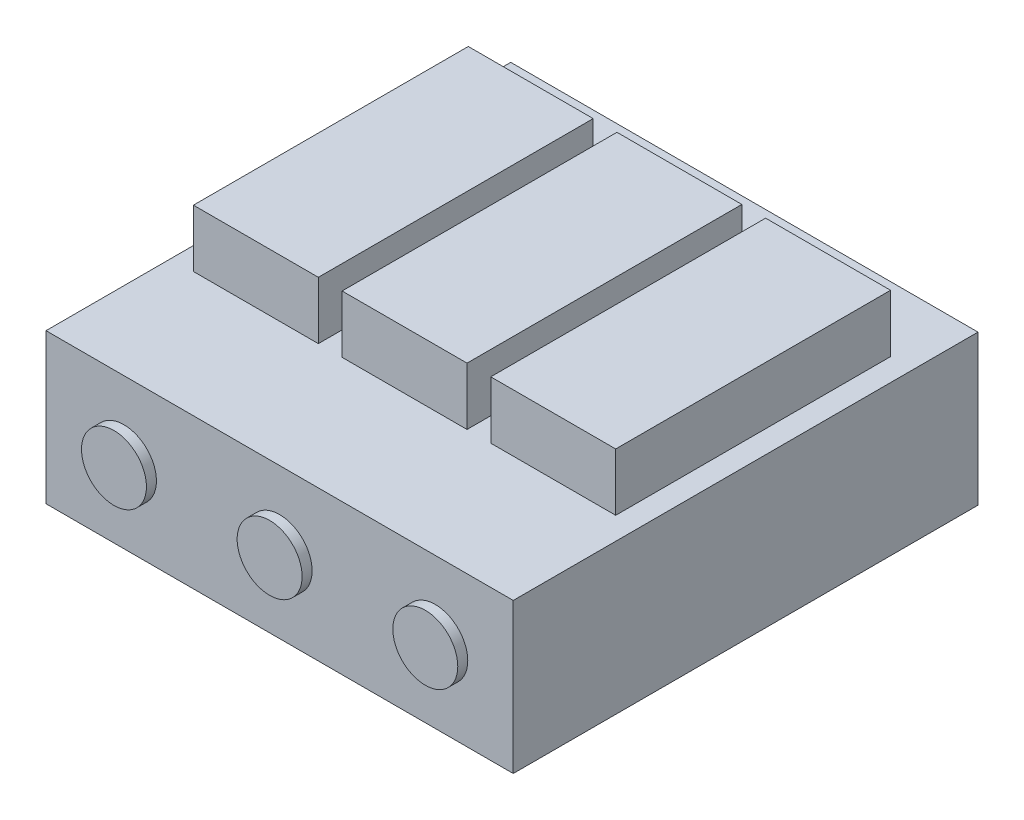
SolidWorks part; units mm, degrees
ref_plane "Front Plane" through (0, 0, 0) normal (0, 0, 1) x (1, 0, 0)
ref_plane "Top Plane" through (0, 0, 0) normal (0, 1, 0) x (1, 0, 0)
ref_plane "Right Plane" through (0, 0, 0) normal (1, 0, 0) x (0, 0, -1)
sketch "SK Housing" plane through (0, 0, 0) normal (0, 1, 0) x (1, 0, 0)
  line L1 (0, 18.6) -> (18.7, 18.6)
  line L2 (0, 18.6) -> (0, 0)
  line L3 (0, 0) -> (18.7, 0)
  line L4 (18.7, 18.6) -> (18.7, 0)
extrude "Housing" add sketch "SK Housing" along normal blind 6 separate body
sketch "SK Levers" plane through (0, 0, 0) normal (0, 1, 0) x (1, 0, 0)
  line L1 (0.9, 16) -> (5.9, 16)
  line L2 (0.9, 16) -> (0.9, 5)
  line L3 (0.9, 5) -> (5.9, 5)
  line L4 (5.9, 16) -> (5.9, 5)
  line L6 (6.85, 16) -> (11.85, 16)
  line L7 (6.85, 16) -> (6.85, 5)
  line L8 (6.85, 5) -> (11.85, 5)
  line L9 (11.85, 16) -> (11.85, 5)
  line L11 (12.8, 16) -> (17.8, 16)
  line L12 (12.8, 16) -> (12.8, 5)
  line L13 (12.8, 5) -> (17.8, 5)
  line L14 (17.8, 16) -> (17.8, 5)
extrude "Levers" add sketch "SK Levers" along normal blind 2.3 from offset 6 separate body
sketch "SK Wire entries" plane through (0, 0, 0) normal (0, 0, 1) x (1, 0, 0)
  circle A0 centre (3.12, 3) radius 1.3
  circle A1 centre (9.35, 3) radius 1.3
  circle A2 centre (15.58, 3) radius 1.3
extrude "Wire entries" add sketch "SK Wire entries" along normal blind 0.4 separate body
